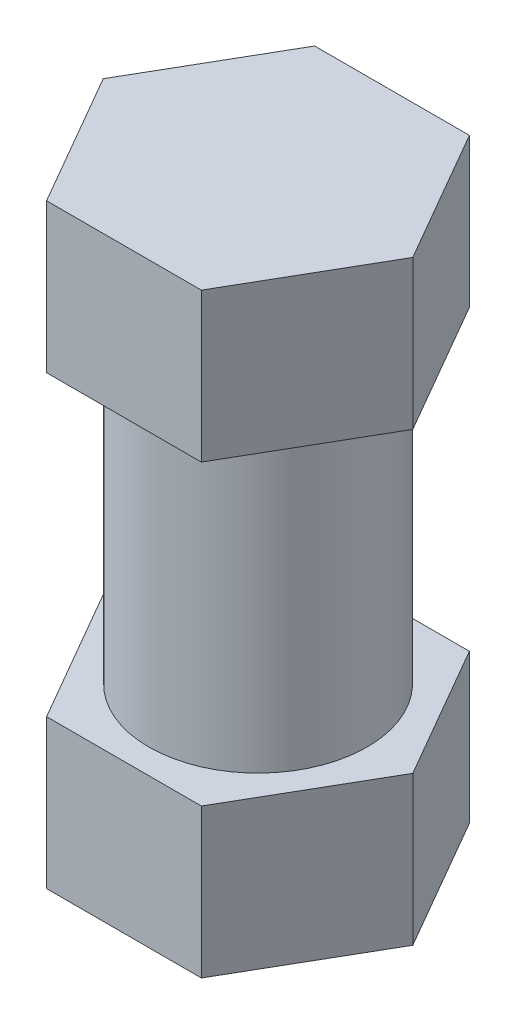
SolidWorks part; units mm, degrees
ref_plane "Front Plane" through (0, 0, 0) normal (0, 0, 1) x (1, 0, 0)
ref_plane "Top Plane" through (0, 0, 0) normal (0, 1, 0) x (1, 0, 0)
ref_plane "Right Plane" through (0, 0, 0) normal (1, 0, 0) x (0, 0, -1)
sketch "Sketch1" plane through (0, 0, 0) normal (0, 1, 0) x (1, 0, 0)
  circle A0 centre (0, 0) radius 2.2
  dimension "D1" = 4.4
extrude "Boss-Extrude1" add sketch "Sketch1" along normal blind 3
sketch "Sketch2" plane through (0, 3, 0) normal (0, 1, 0) x (1, 0, 0)
  line L0 (0, 0) -> (3.1177, 0) construction
  line L1 (-1.5588, 2.7) -> (-3.1177, 0)
  line L2 (-3.1177, 0) -> (-1.5588, -2.7)
  line L3 (-1.5588, -2.7) -> (1.5588, -2.7)
  line L4 (1.5588, -2.7) -> (3.1177, 0)
  line L5 (3.1177, 0) -> (1.5588, 2.7)
  line L6 (1.5588, 2.7) -> (-1.5588, 2.7)
  circle A0 centre (0, 0) radius 2.7 construction
  dimension "D1" = 5.4
extrude "Boss-Extrude2" add sketch "Sketch2" along normal blind 3
mirror "Mirror1" about plane through (0, 0, 0) normal (0, 1, 0) of "Boss-Extrude2", "Boss-Extrude1"
